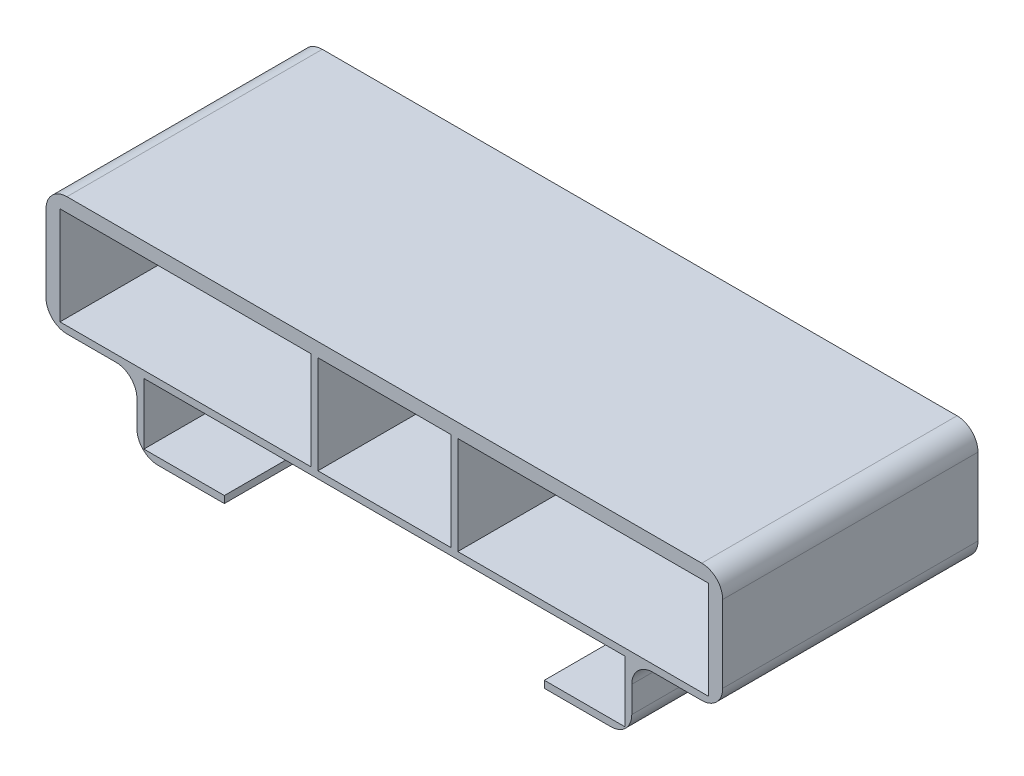
SolidWorks part; units mm, degrees
ref_plane "Front Plane" through (0, 0, 0) normal (0, 0, 1) x (1, 0, 0)
ref_plane "Top Plane" through (0, 0, 0) normal (0, 1, 0) x (1, 0, 0)
ref_plane "Right Plane" through (0, 0, 0) normal (1, 0, 0) x (0, 0, -1)
sketch "Sketch2" plane through (0, 0, 0) normal (0, 0, 1) x (1, 0, 0)
  line L1 (0, 0) -> (141.5, 0)
  line L2 (0, 0) -> (0, -21.5)
  line L3 (0, -21.5) -> (141.5, -21.5)
  line L4 (141.5, 0) -> (141.5, -21.5)
  dimension "D1" = 141.5
  dimension "D2" = 21.5
extrude "Boss-Extrude1" add sketch "Sketch2" along normal blind 73
shell "Shell1" thickness 2
sketch "Sketch3" plane through (0, 0, 73) normal (0, 0, 1) x (1, 0, 0)
  line L0 (2, -19.5) -> (139.5, -19.5) construction
  line L1 (25, -19.5) -> (116.5, -19.5)
  line L2 (25, -19.5) -> (25, -21.5)
  line L3 (25, -21.5) -> (116.5, -21.5)
  line L4 (116.5, -19.5) -> (116.5, -21.5)
  line L5 (0, -21.5) -> (141.5, -21.5) construction
  line L6 (25, -21.5) -> (0, -21.5) construction
  line L7 (116.5, -21.5) -> (141.5, -21.5) construction
  dimension "D1" = 25
extrude "Cut-Extrude1" cut sketch "Sketch3" against normal up to surface (73 mm away) up to face at (70.75, -10.75, 0)
sketch "Sketch7" plane through (0, 0, 0) normal (-1, 0, 0) x (0, 0, 1)
  line L0 (73, 0) -> (73, -21.5) construction
  line L1 (0, 0) -> (73, 0)
  line L2 (0, 0) -> (0, -2)
  line L3 (0, -2) -> (73, -2)
  line L4 (73, 0) -> (73, -2)
  dimension "D1" = 2
extrude "Boss-Extrude5" add sketch "Sketch7" along normal blind 26
sketch "Sketch8" plane through (141.5, 0, 0) normal (1, 0, 0) x (0, 0, -1)
  line L0 (0, -21.5) -> (0, 0) construction
  line L1 (-73, 0) -> (0, 0)
  line L2 (-73, 0) -> (-73, -2)
  line L3 (-73, -2) -> (0, -2)
  line L4 (0, 0) -> (0, -2)
  dimension "D1" = 2
extrude "Boss-Extrude6" add sketch "Sketch8" along normal blind 26
sketch "Sketch9" plane through (0, 0, 0) normal (0, 1, 0) x (1, 0, 0)
  line L0 (167.5, -73) -> (-26, -73) construction
  line L1 (167.5, 0) -> (163.5, 0)
  line L2 (167.5, 0) -> (167.5, -73)
  line L3 (167.5, -73) -> (163.5, -73)
  line L4 (163.5, 0) -> (163.5, -73)
  line L6 (-26, 0) -> (-22, 0)
  line L7 (-26, 0) -> (-26, -73)
  line L8 (-26, -73) -> (-22, -73)
  line L9 (-22, 0) -> (-22, -73)
  dimension "D1" = 4
  dimension "D2" = 4
extrude "Boss-Extrude7" add sketch "Sketch9" along normal blind 28
sketch "Sketch10" plane through (0, 28, 0) normal (0, 1, 0) x (1, 0, 0)
  line L1 (-26, 0) -> (167.5, 0)
  line L2 (-26, 0) -> (-26, -73)
  line L3 (-26, -73) -> (167.5, -73)
  line L4 (167.5, 0) -> (167.5, -73)
extrude "Boss-Extrude8" add sketch "Sketch10" along normal blind 4
sketch "Sketch11" plane through (0, 0, 0) normal (0, 1, 0) x (1, 0, 0)
  line L0 (167.5, 0) -> (-26, 0) construction
  line L1 (49.75, 0) -> (51.75, 0)
  line L2 (49.75, 0) -> (49.75, -73)
  line L3 (49.75, -73) -> (51.75, -73)
  line L4 (51.75, 0) -> (51.75, -73)
  line L5 (-26, -73) -> (167.5, -73) construction
  line L6 (49.75, 0) -> (-26, 0) construction
  line L7 (89.75, 0) -> (91.75, 0)
  line L8 (89.75, 0) -> (89.75, -73)
  line L9 (89.75, -73) -> (91.75, -73)
  line L10 (91.75, 0) -> (91.75, -73)
  line L11 (91.75, 0) -> (167.5, 0) construction
  dimension "D1" = 2
  dimension "D2" = 38
extrude "Boss-Extrude9" add sketch "Sketch11" along normal up to surface (28 mm away) up to face at (70.75, 28, 36.5)
sketch "Sketch13" plane through (0, 0, 0) normal (0, 1, 0) x (1, 0, 0)
  line L0 (51.75, -73) -> (51.75, 0) construction
  line L1 (51.75, -2) -> (89.75, -2)
  line L2 (51.75, -2) -> (51.75, 0)
  line L3 (51.75, 0) -> (89.75, 0)
  line L4 (89.75, -2) -> (89.75, 0)
  dimension "D1" = 2
extrude "Boss-Extrude10" add sketch "Sketch13" along normal up to surface (28 mm away) up to face at (70.75, 28, 36.5)
fillet "Fillet1" radius 6 8 edges at (0, -2, 36.5) (141.5, -2, 36.5) (0, -21.5, 36.5) (141.5, -21.5, 36.5) (167.5, 32, 36.5) (167.5, -2, 36.5) (-26, 32, 36.5) (-26, -2, 36.5)
